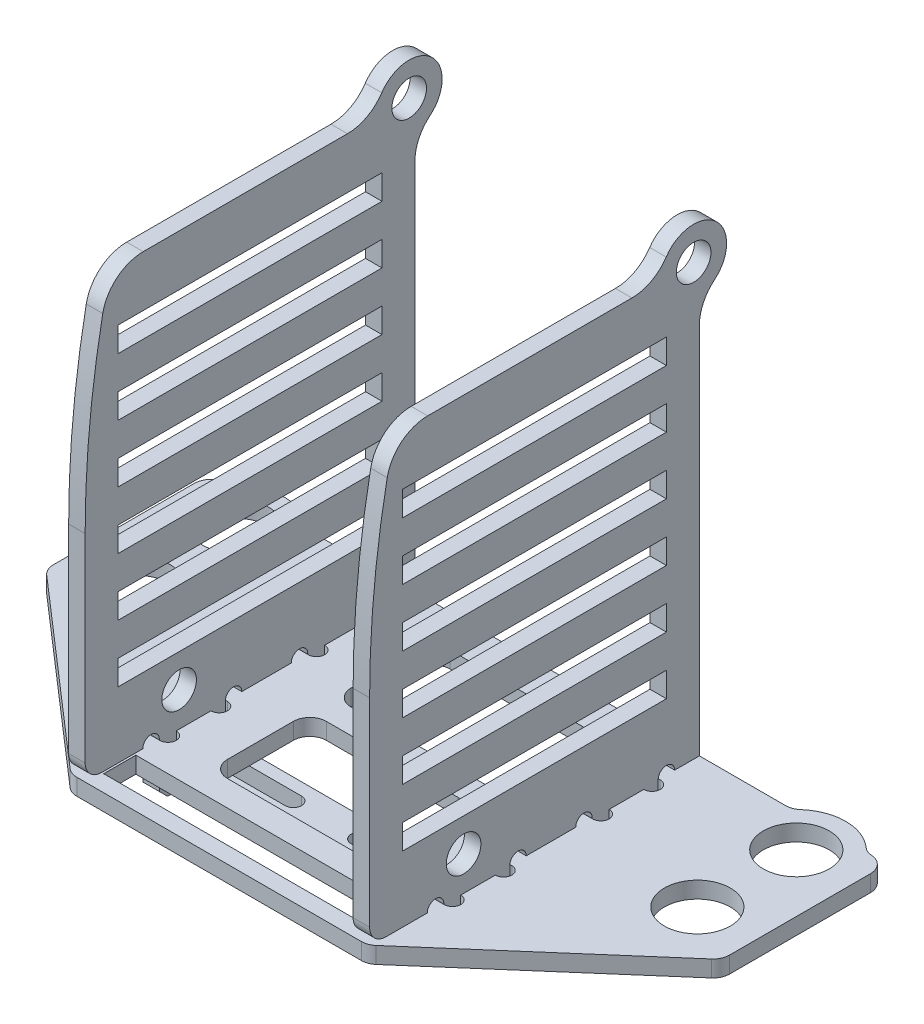
SolidWorks part; units mm, degrees
material "碳板"
ref_plane "前视基准面" through (0, 0, 0) normal (0, 0, 1) x (1, 0, 0)
ref_plane "上视基准面" through (0, 0, 0) normal (0, 1, 0) x (1, 0, 0)
ref_plane "右视基准面" through (0, 0, 0) normal (1, 0, 0) x (0, 0, -1)
sketch "草图1" plane through (0, 0, 0) normal (0, 1, 0) x (1, 0, 0)
  line L0 (0, 71.4335) -> (0, -59.6674) construction
  line L1 (-88.5603, 0) -> (80.2367, 0) construction
  line L2 (-41, -10) -> (-41, 10)
  line L3 (-41, 10) -> (-38.4721, 10)
  line L4 (-29.5279, 10) -> (29.5279, 10)
  line L5 (-18.4, -12.9) -> (-16.1, -12.9)
  line L6 (-16, 15) -> (16, 15) construction
  line L7 (-16, 15) -> (-16, -28) construction
  line L8 (-16, -28) -> (16, -28) construction
  line L9 (16, 15) -> (16, -28) construction
  line L10 (-16, 15) -> (16, -28) construction
  line L11 (-16, -28) -> (16, 15) construction
  line L12 (-18.4, 5.1) -> (-16.1, 5.1)
  line L13 (-18.4, 3.1) -> (-18.4, -1.1)
  line L14 (-18.4, -3.1) -> (-16.1, -3.1)
  line L15 (-16.1, 3.1) -> (-16.1, -1.1)
  line L16 (-18.4, 5.1) -> (-16.1, -3.1) construction
  line L17 (-18.4, -3.1) -> (-16.1, 5.1) construction
  line L18 (-16.1, -14.9) -> (-16.1, -19.1)
  line L19 (-18.4, -21.1) -> (-16.1, -21.1)
  line L20 (-18.4, -14.9) -> (-18.4, -19.1)
  line L21 (-18.4, 5.1) -> (-18.4, -12.9) construction
  line L22 (-41, -10) -> (-18, -30)
  line L23 (-18, -30) -> (18, -30)
  line L24 (18.4, -14.9) -> (18.4, -19.1)
  line L25 (18.4, -21.1) -> (16.1, -21.1)
  line L26 (16.1, -14.9) -> (16.1, -19.1)
  line L27 (18.4, -12.9) -> (16.1, -12.9)
  line L28 (18.4, 3.1) -> (18.4, -1.1)
  line L29 (18.4, -3.1) -> (16.1, -3.1)
  line L30 (16.1, 3.1) -> (16.1, -1.1)
  line L31 (18.4, 5.1) -> (16.1, 5.1)
  line L32 (41, 10) -> (38.4721, 10)
  line L33 (41, -10) -> (41, 10)
  line L34 (41, -10) -> (18, -30)
  line L35 (-10, -9) -> (-10, -21)
  line L36 (-16, -24.1) -> (16, -24.1)
  line L37 (-16, -24.1) -> (-16, -28)
  line L38 (-16, -28) -> (16, -28)
  line L39 (16, -24.1) -> (16, -28)
  line L40 (-16, -24.1) -> (16, -28) construction
  line L41 (-16, -28) -> (16, -24.1) construction
  line L42 (-10, 6) -> (10, 6)
  line L43 (-10, 6) -> (-10, -6)
  line L44 (-10, -6) -> (10, -6)
  line L45 (10, 6) -> (10, -6)
  line L46 (-10, 6) -> (10, -6) construction
  line L47 (-10, -6) -> (10, 6) construction
  line L48 (-10, -9) -> (10, -9)
  line L49 (10, -9) -> (10, -21)
  line L50 (-10, -21) -> (10, -21)
  line L51 (-10, 6) -> (-10, -9) construction
  circle A0 centre (-34, 6) radius 4
  circle A1 centre (-34, -6) radius 4
  circle A2 centre (34, -6) radius 4
  circle A3 centre (34, 6) radius 4
  arc A4 (-29.5279, 10) -> (-38.4721, 10) centre (-34, 6) ccw
  arc A5 (-18.4, 5.1) -> (-18.4, 3.1) centre (-18.4, 4.1) ccw
  arc A6 (-18.4, -1.1) -> (-18.4, -3.1) centre (-18.4, -2.1) ccw
  arc A7 (-16.1, 3.1) -> (-16.1, 5.1) centre (-16.1, 4.1) ccw
  arc A8 (-16.1, -3.1) -> (-16.1, -1.1) centre (-16.1, -2.1) ccw
  arc A9 (-16.1, -14.9) -> (-16.1, -12.9) centre (-16.1, -13.9) ccw
  arc A10 (-16.1, -21.1) -> (-16.1, -19.1) centre (-16.1, -20.1) ccw
  arc A11 (-18.4, -19.1) -> (-18.4, -21.1) centre (-18.4, -20.1) ccw
  arc A12 (-18.4, -12.9) -> (-18.4, -14.9) centre (-18.4, -13.9) ccw
  arc A13 (18.4, -12.9) -> (18.4, -14.9) centre (18.4, -13.9) cw
  arc A14 (18.4, -19.1) -> (18.4, -21.1) centre (18.4, -20.1) cw
  arc A15 (16.1, -21.1) -> (16.1, -19.1) centre (16.1, -20.1) cw
  arc A16 (16.1, -14.9) -> (16.1, -12.9) centre (16.1, -13.9) cw
  arc A17 (18.4, 5.1) -> (18.4, 3.1) centre (18.4, 4.1) cw
  arc A18 (18.4, -1.1) -> (18.4, -3.1) centre (18.4, -2.1) cw
  arc A19 (16.1, -3.1) -> (16.1, -1.1) centre (16.1, -2.1) cw
  arc A20 (16.1, 3.1) -> (16.1, 5.1) centre (16.1, 4.1) cw
  arc A21 (29.5279, 10) -> (38.4721, 10) centre (34, 6) cw
  point P16 (-17.25, 1)
  point P18 (0, -6.5)
  point P35 (0, -26.05)
  point P77 (0, 10)
  point P81 (0, -30)
  point P86 (0, 0)
  dimension "D1" = 8
  dimension "D5" = 12
  dimension "D11" = 2
  dimension "D2" = 12
  dimension "D3" = 68
  dimension "D4" = 10
  dimension "D6" = 7
  dimension "D7" = 5
  dimension "D8" = 32
  dimension "D9" = 28
  dimension "D10" = 2.3
  dimension "D12" = 8.2
  dimension "D13" = 0.1
  dimension "D14" = 9
  dimension "D16" = 18
  dimension "D17" = 2
  dimension "D18" = 36
  dimension "D19" = 20
  dimension "D20" = 3
  dimension "D21" = 32
  dimension "D22" = 4
  dimension "D23" = 20
  dimension "D24" = 12
  dimension "D26" = 15
  dimension "D15" = 2
  dimension "D25" = 2
extrude "凸台-拉伸1" add sketch "草图1" along normal blind 2
fillet "圆角1" radius 2 14 edges at (-41, 1, -10) (41, 1, -10) (41, 1, 10) (18, 1, 30) (-18, 1, 30) (-41, 1, 10) (10, 1, 21) (10, 1, 9) (-10, 1, 21) (-10, 1, 9) (10, 1, -6) (-10, 1, 6) (10, 1, 6) (-10, 1, -6)
fillet "圆角2" radius 2 4 edges at (38.4721, 1, -10) (29.5279, 1, -10) (-29.5279, 1, -10) (-38.4721, 1, -10)
ref_plane "基准面1" through (-17.25, 0, 0) normal (1, 0, 0) x (0, 0, -1)
sketch "草图2" plane through (-17.25, 0, 0) normal (1, 0, 0) x (0, 0, -1)
  line L0 (1, 0) -> (1, 2) construction
  line L1 (-1.1, 2) -> (3.1, 2) construction
  line L2 (-1.1, 2) -> (3.1, 2) construction
  line L3 (-1.1, 0) -> (3.1, 0) construction
  line L4 (-1.1, 0) -> (3.1, 0) construction
  line L5 (5, 0) -> (-3, 0)
  line L6 (-3, 0) -> (-3, 2)
  line L7 (5, 0) -> (5, 2)
  line L8 (-5, 2) -> (-11, 2)
  line L9 (7, 2) -> (10, 2)
  line L10 (-19.1, 2) -> (-14.9, 2) construction
  line L11 (-19.1, 2) -> (-14.9, 2) construction
  line L12 (-19.1, 0) -> (-14.9, 0) construction
  line L13 (-19.1, 0) -> (-14.9, 0) construction
  line L14 (-17, 0) -> (-17, 2) construction
  line L15 (-21, -4.5) -> (-13, -4.5)
  line L16 (-13, -4.5) -> (-13, 2)
  line L17 (-21, -4.5) -> (-21, 2)
  line L18 (-23, 2) -> (-30, 2)
  line L19 (-14.4, -0.2) -> (-19.6, -0.2)
  line L20 (-14.4, -0.2) -> (-14.4, -2.5)
  line L21 (-14.4, -2.5) -> (-19.6, -2.5)
  line L22 (-19.6, -0.2) -> (-19.6, -2.5)
  line L23 (-14.4, -0.2) -> (-19.6, -2.5) construction
  line L24 (-14.4, -2.5) -> (-19.6, -0.2) construction
  line L25 (10, 2) -> (10, 50.2517)
  line L26 (-30, 2) -> (-30, 54.19)
  line L27 (-30, 54.19) -> (5.3, 54.19)
  line L28 (6, 20) -> (6, 17)
  line L29 (6, 13) -> (-26, 13)
  line L30 (6, 13) -> (6, 10)
  line L31 (6, 10) -> (-26, 10)
  line L32 (-26, 13) -> (-26, 10)
  line L33 (6, 13) -> (-26, 10) construction
  line L34 (6, 10) -> (-26, 13) construction
  line L35 (6, 20) -> (-26, 20)
  line L36 (-26, 20) -> (-26, 17)
  line L37 (6, 17) -> (-26, 17)
  line L38 (6, 27) -> (6, 24)
  line L39 (6, 27) -> (-26, 27)
  line L40 (-26, 27) -> (-26, 24)
  line L41 (6, 24) -> (-26, 24)
  line L42 (6, 34) -> (6, 31)
  line L43 (6, 34) -> (-26, 34)
  line L44 (-26, 34) -> (-26, 31)
  line L45 (6, 31) -> (-26, 31)
  line L46 (6, 41) -> (6, 38)
  line L47 (6, 41) -> (-26, 41)
  line L48 (-26, 41) -> (-26, 38)
  line L49 (6, 38) -> (-26, 38)
  line L50 (6, 48) -> (6, 45)
  line L51 (6, 48) -> (-26, 48)
  line L52 (-26, 48) -> (-26, 45)
  line L53 (6, 45) -> (-26, 45)
  line L54 (6, 13) -> (6, 20) construction
  arc A0 (-3, 2) -> (-5, 2) centre (-4, 2) ccw
  arc A1 (5, 2) -> (7, 2) centre (6, 2) cw
  arc A2 (-11, 2) -> (-13, 2) centre (-12, 2) ccw
  arc A3 (-23, 2) -> (-21, 2) centre (-22, 2) cw
  circle A4 centre (-15.3145, -0.6045) radius 1
  circle A5 centre (-15.3145, -2.0955) radius 1
  circle A6 centre (-18.6855, -0.6045) radius 1
  circle A7 centre (-18.6855, -2.0955) radius 1
  circle A8 centre (-18.6, 6) radius 2.1
  circle A9 centre (9.3, 54.19) radius 2.1
  arc A10 (10, 50.2517) -> (5.3, 54.19) centre (9.3, 54.19) ccw
  arc A11 (-27, 54.19) -> (-30, 28.095) centre (84.9915, 28.095) ccw
  point P11 (-17, -1.35)
  point P33 (-17, -4.5)
  point P55 (-10, 11.5)
  dimension "D1" = 2
  dimension "D5" = 2
  dimension "D9" = 2
  dimension "D13" = 4.2
  dimension "D15" = 27.9
  dimension "D18" = 8
  dimension "D19" = 3
  dimension "D2" = 8
  dimension "D3" = 2
  dimension "D4" = 3
  dimension "D6" = 8
  dimension "D7" = 4.5
  dimension "D8" = 2.3
  dimension "D10" = 5.2
  dimension "D11" = 0.2
  dimension "D12" = 40
  dimension "D14" = 4
  dimension "D16" = 48.19
  dimension "D17" = 0.7
  dimension "D20" = 4
  dimension "D21" = 3
  dimension "D22" = 4
  dimension "D23" = 4
  dimension "D25" = 7
  dimension "D24" = 6
extrude "凸台-拉伸2" add sketch "草图2" along normal mid plane 2 separate body contours L25 A10 L27 L26 L18 A3 L17 L15 L16 A2 L8 A0 L6 L5 L7 A1 L9 A7 L22 A6 L19 A4 L20 A5 L21 A8 A9
fillet "圆角3" radius 5 3 edges at (-17.25, 50.2517, -10) (-17.25, 54.19, 27) (-17.25, 54.19, -5.3)
fillet "圆角4" radius 2 1 edges at (-17.25, 2, 30)
chamfer "倒角1" distance 1 angle 45 2 edges at (-17.25, -4.5, 21) (-17.25, -4.5, 13)
mirror "镜向1" about plane through (0, 0, 0) normal (1, 0, 0) of bodies 107
ref_plane "基准面2" through (0, -1.35, 0) normal (0, -1, 0) x (-1, 0, 0)
sketch "草图3" plane through (0, -1.35, 0) normal (0, -1, 0) x (-1, 0, 0)
  line L0 (0, 21.9599) -> (0, -52.803) construction
  line L1 (18.25, -16.2291) -> (18.25, -17.7709) construction
  line L2 (18.25, -16.2291) -> (18.25, -17.7709) construction
  line L3 (18.25, -17) -> (-21.2113, -17) construction
  line L4 (20.25, -18.5) -> (20.25, -15.5)
  line L5 (20.25, -15.5) -> (18.25, -14.5)
  line L6 (18.25, -14.5) -> (-18.25, -14.5)
  line L7 (20.25, -18.5) -> (18.25, -19.5)
  line L8 (18.25, -19.5) -> (-18.25, -19.5)
  line L9 (-20.25, -18.5) -> (-18.25, -19.5)
  line L10 (-20.25, -18.5) -> (-20.25, -15.5)
  line L11 (-20.25, -15.5) -> (-18.25, -14.5)
  line L12 (14, -17) -> (4, -17) construction
  line L13 (14, -18) -> (4, -18)
  line L14 (14, -16) -> (4, -16)
  line L15 (-14, -17) -> (-4, -17) construction
  line L16 (-14, -18) -> (-4, -18)
  line L17 (-14, -16) -> (-4, -16)
  arc A0 (14, -18) -> (14, -16) centre (14, -17) ccw
  arc A1 (4, -16) -> (4, -18) centre (4, -17) ccw
  arc A2 (-14, -18) -> (-14, -16) centre (-14, -17) cw
  arc A3 (-4, -16) -> (-4, -18) centre (-4, -17) cw
  point P12 (9, -17)
  point P15 (20.25, -17)
  point P18 (0, -19.5)
  point P21 (0, -14.5)
  point P25 (11.3057, -17)
  point P26 (8.0135, -17)
  point P29 (-9, -17)
  dimension "D1" = 5
  dimension "D2" = 2
  dimension "D3" = 3
  dimension "D4" = 2
  dimension "D5" = 10
  dimension "D6" = 8
extrude "凸台-拉伸3" add sketch "草图3" along normal mid plane 2 separate body
